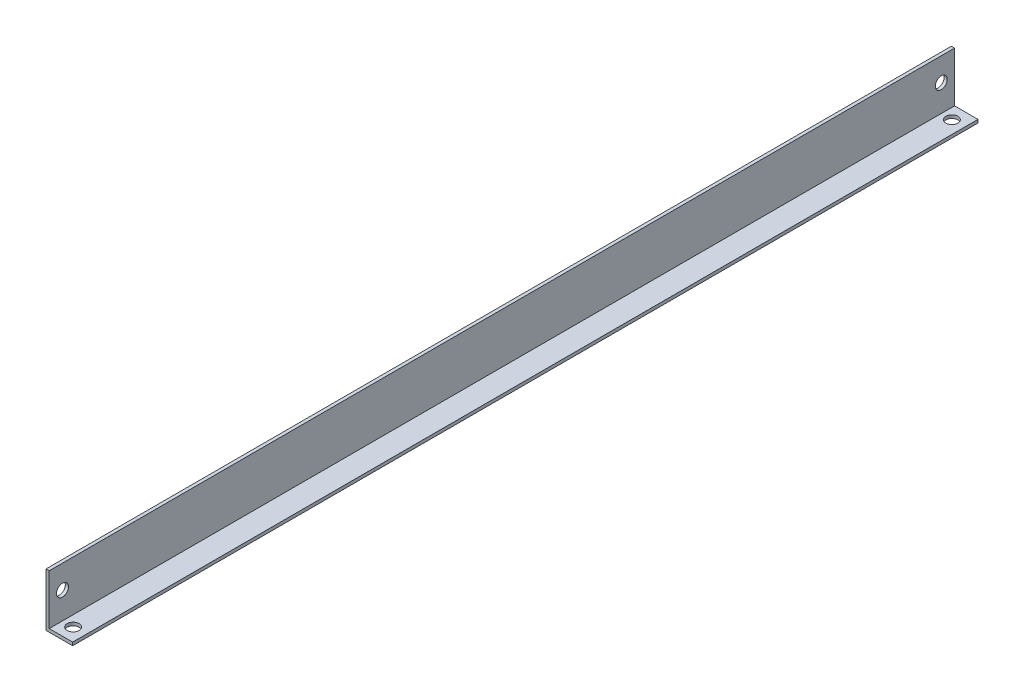
SolidWorks part; units mm, degrees
material "Д16Т ГОСТ 4784-74"
ref_plane "Спереди" through (0, 0, 0) normal (0, 0, 1) x (1, 0, 0)
ref_plane "Сверху" through (0, 0, 0) normal (0, 1, 0) x (1, 0, 0)
ref_plane "Справа" through (0, 0, 0) normal (1, 0, 0) x (0, 0, -1)
sketch "Эскиз1" plane through (0, 0, 0) normal (0, 0, 1) x (1, 0, 0)
  line L0 (0, 0) -> (0, 20)
  line L1 (0, 20) -> (1.2, 20)
  line L2 (1.2, 20) -> (1.2, 1.2)
  line L3 (1.2, 1.2) -> (10, 1.2)
  line L4 (10, 1.2) -> (10, 0)
  line L5 (10, 0) -> (0, 0)
  dimension "D1" = 1.2
  dimension "D2" = 20
  dimension "D3" = 10
extrude "Бобышка-Вытянуть1" add sketch "Эскиз1" along normal blind 340
hole_wizard "Отверстие с зазором M41" positions "Эскиз3" profile "Эскиз2" hole size "M4" standard "DIN"
sketch "Эскиз3" plane through (0, 0, 0) normal (-1, 0, 0) x (0, 0, 1)
  line L1 (340, 20) -> (340, 0) construction
  line L2 (0, 20) -> (0, 0) construction
  line L3 (340, 1.2) -> (0, 1.2) construction
  point P0 (335, 11.2)
  point P1 (5, 11.2)
  dimension "D1" = 10
  dimension "D2" = 5
  dimension "D3" = 5
sketch "Эскиз2" plane through (0, 11.2, 335) normal (0, 1, 0) x (0, 0, 1)
  line L0 (0, 0) -> (0, 6.3519)
  line L1 (0, 6.3519) -> (2.25, 5)
  line L2 (2.25, 5) -> (2.25, 0)
  line L5 (2.25, 0) -> (0, 0)
  line L10 (0, 6.3519) -> (-2.25, 5) construction
  line L11 (0, -6.35) -> (0, 107.95) construction
  dimension "Диаметр отверстия" = 4.5
  dimension "Глубина отверстия" = 5
  dimension "Угол заточки сверла" = 118
hole_wizard "Отверстие с зазором M42" positions "Эскиз5" profile "Эскиз4" hole size "M4" standard "DIN"
sketch "Эскиз5" plane through (0, 0, 0) normal (0, -1, 0) x (1, 0, 0)
  line L0 (1.2, 340) -> (1.2, 0) construction
  line L1 (0, 340) -> (10, 340) construction
  line L2 (0, 0) -> (10, 0) construction
  point P0 (5.2, 5)
  point P1 (5.2, 335)
  dimension "D1" = 4
  dimension "D2" = 5
  dimension "D3" = 5
sketch "Эскиз4" plane through (5.2, 0, 5) normal (1, 0, 0) x (0, 0, -1)
  line L0 (0, 0) -> (0, 6.3519)
  line L1 (0, 6.3519) -> (2.25, 5)
  line L2 (2.25, 5) -> (2.25, 0)
  line L5 (2.25, 0) -> (0, 0)
  line L10 (0, 6.3519) -> (-2.25, 5) construction
  line L11 (0, -6.35) -> (0, 107.95) construction
  dimension "Диаметр отверстия" = 4.5
  dimension "Глубина отверстия" = 5
  dimension "Угол заточки сверла" = 118
